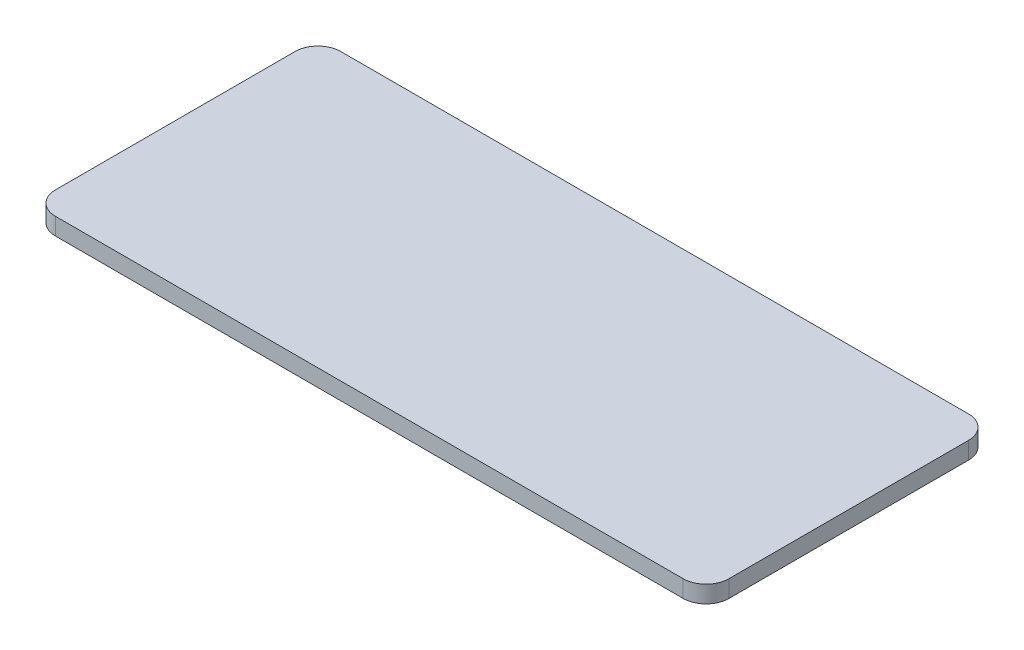
SolidWorks part; units mm, degrees
ref_plane "前视基准面" through (0, 0, 0) normal (0, 0, 1) x (1, 0, 0)
ref_plane "上视基准面" through (0, 0, 0) normal (0, 1, 0) x (1, 0, 0)
ref_plane "右视基准面" through (0, 0, 0) normal (1, 0, 0) x (0, 0, -1)
sketch "草图1" plane through (0, 0, 0) normal (0, 1, 0) x (1, 0, 0)
  line L0 (385.9126, 395.6415) -> (975.9126, 395.6415)
  line L1 (975.9126, 395.6415) -> (975.9126, 645.6415)
  line L2 (975.9126, 645.6415) -> (385.9126, 645.6415)
  line L3 (385.9126, 645.6415) -> (385.9126, 395.6415)
extrude "凸台-拉伸1" add sketch "草图1" along normal blind 15
fillet "圆角1" radius 20 4 edges at (975.9126, 7.5, -645.6415) (975.9126, 7.5, -395.6415) (385.9126, 7.5, -645.6415) (385.9126, 7.5, -395.6415)
